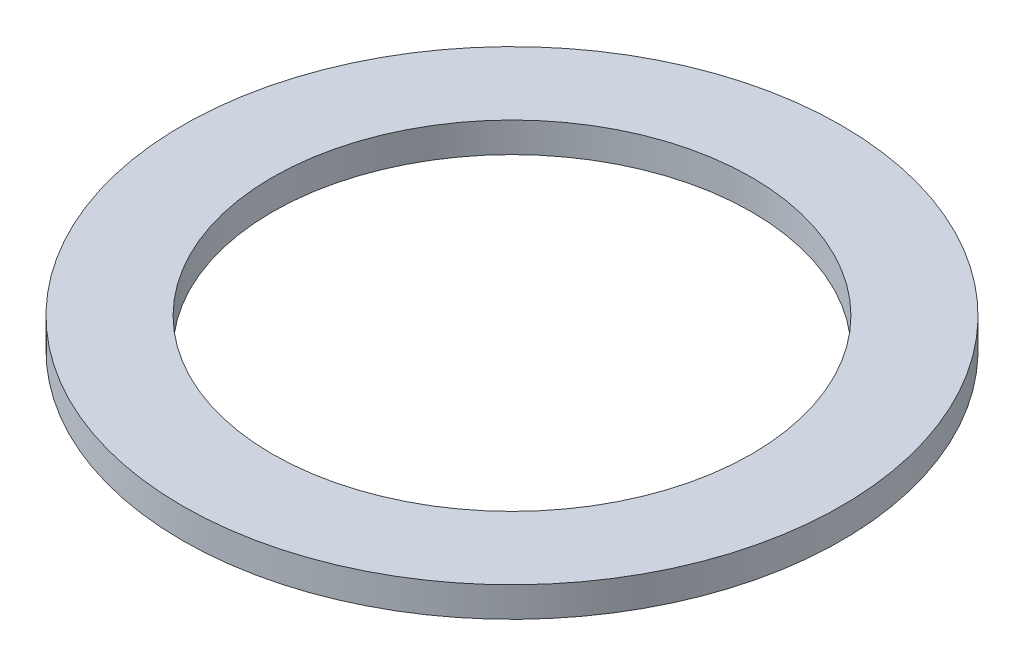
SolidWorks part; units mm, degrees
ref_plane "Front Plane" through (0, 0, 0) normal (0, 0, 1) x (1, 0, 0)
ref_plane "Top Plane" through (0, 0, 0) normal (0, 1, 0) x (1, 0, 0)
ref_plane "Right Plane" through (0, 0, 0) normal (1, 0, 0) x (0, 0, -1)
sketch "Sketch1" plane through (0, 0, 0) normal (0, 1, 0) x (1, 0, 0)
  circle A0 centre (0, 0) radius 11
  dimension "OD" = 22
extrude "Boss-Extrude1" add sketch "Sketch1" along normal blind 1
sketch "Sketch5" plane through (0, 1, 0) normal (0, 1, 0) x (-1, 0, 0)
  circle A0 centre (0, 0) radius 8
  dimension "ID" = 16
extrude "Cut-Extrude1" cut sketch "Sketch5" against normal through all
